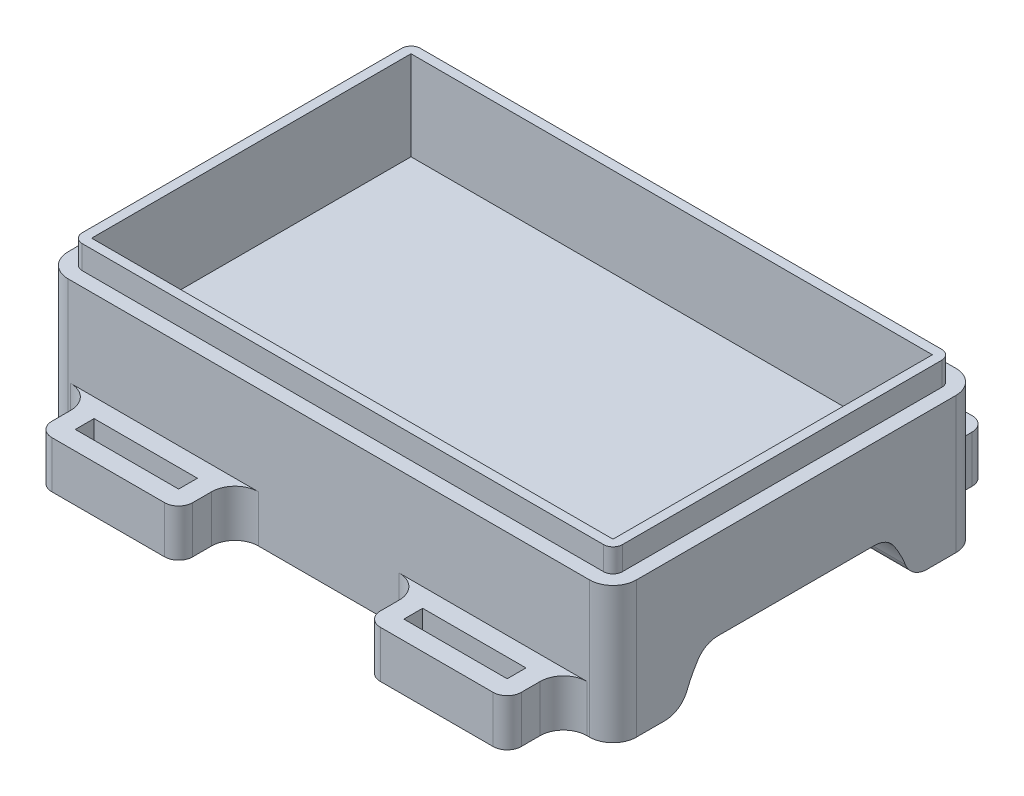
SolidWorks part; units mm, degrees
ref_plane "Alzado" through (0, 0, 0) normal (0, 0, 1) x (1, 0, 0)
ref_plane "Planta" through (0, 0, 0) normal (0, 1, 0) x (1, 0, 0)
ref_plane "Vista lateral" through (0, 0, 0) normal (1, 0, 0) x (0, 0, -1)
sketch "Croquis2" plane through (0, 0, 0) normal (0, 1, 0) x (1, 0, 0)
  line L1 (-55.5, 34) -> (55.5, 34)
  line L2 (-55.5, 34) -> (-55.5, -34)
  line L3 (-55.5, -34) -> (55.5, -34)
  line L4 (55.5, 34) -> (55.5, -34)
  line L12 (60.5, 39) -> (-60.5, 39)
  line L13 (-60.5, 39) -> (-60.5, -39)
  line L14 (-60.5, -39) -> (60.5, -39)
  line L15 (60.5, -39) -> (60.5, 39)
  point P4 (0, -34)
  point P6 (-55.5, 0)
  point P9 (0, -39)
  point P11 (-60.5, 0)
  point P13 (78.4837, 47.2518)
  dimension "D1" = 111
  dimension "D2" = 68
  dimension "D3" = 5
  dimension "D4" = 5
extrude "Saliente-Extruir2" add sketch "Croquis2" against normal blind 19
sketch "Croquis4" plane through (0, -19, 0) normal (0, -1, 0) x (1, 0, 0)
  line L4 (60.5, 39) -> (-60.5, 39)
  line L5 (-60.5, 39) -> (-60.5, -39)
  line L6 (-60.5, -39) -> (60.5, -39)
  line L7 (60.5, -39) -> (60.5, 39)
  line L8 (60.5, 39) -> (-60.5, 39)
  line L9 (-60.5, 39) -> (-60.5, -39)
  line L10 (-60.5, -39) -> (60.5, -39)
  line L11 (60.5, -39) -> (60.5, 39)
  dimension "D1" = 0
extrude "Saliente-Extruir3" add sketch "Croquis4" along normal blind 5
sketch "Croquis6" plane through (0, 0, 0) normal (1, 0, 0) x (0, 0, -1)
  line L0 (-19.2094, -24) -> (19.2094, -24) construction
  line L1 (-39, -24) -> (-19.2094, -24)
  line L2 (-39, -24) -> (-39, -34)
  line L3 (-39, -34) -> (-24.2693, -34)
  line L4 (39, -24) -> (39, -34)
  line L5 (19.2094, -24) -> (39, -24)
  line L6 (24.2693, -34) -> (39, -34)
  line L9 (39, -24) -> (-39, -24) construction
  circle A0 centre (0, -40) radius 25 construction
  arc A1 (-19.2094, -24) -> (-24.2693, -34) centre (0, -40) ccw
  arc A2 (19.2094, -24) -> (24.2693, -34) centre (0, -40) cw
  dimension "D2" = 50
  dimension "D1" = 40
  dimension "D3" = 10
extrude "Saliente-Extruir4" add sketch "Croquis6" along normal through all and the other way through all
fillet "Redondeo2" radius 5 4 edges at (0, -34, 24.2693) (0, -34, -24.2693) (0, -24, 19.2094) (0, -24, -19.2094)
sketch "Croquis7" plane through (0, -24, 0) normal (0, -1, 0) x (1, 0, 0)
  line L1 (-49.975, 39) -> (-19.975, 39)
  line L2 (-49.975, 39) -> (-49.975, 51)
  line L3 (-49.975, 51) -> (-19.975, 51)
  line L4 (-19.975, 39) -> (-19.975, 51)
  line L14 (0, 40) -> (0, -40) construction
  line L19 (-60.5, 0) -> (60.5, 0) construction
  line L20 (-60.5, 16.7033) -> (-60.5, -16.7033) construction
  line L21 (60.5, -16.7033) -> (60.5, 16.7033) construction
  line L22 (-49.975, -51) -> (-19.975, -51)
  line L23 (-19.975, -39) -> (-19.975, -51)
  line L24 (-49.975, -39) -> (-19.975, -39)
  line L25 (-49.975, -39) -> (-49.975, -51)
  line L26 (49.975, -39) -> (49.975, -51)
  line L27 (49.975, -39) -> (19.975, -39)
  line L28 (19.975, -39) -> (19.975, -51)
  line L29 (49.975, -51) -> (19.975, -51)
  line L30 (49.975, 51) -> (19.975, 51)
  line L31 (19.975, 39) -> (19.975, 51)
  line L32 (49.975, 39) -> (19.975, 39)
  line L33 (49.975, 39) -> (49.975, 51)
  line L34 (-45.975, -47) -> (-23.975, -47)
  line L35 (-23.975, -43) -> (-23.975, -47)
  line L36 (-45.975, -43) -> (-23.975, -43)
  line L37 (-45.975, -43) -> (-45.975, -47)
  line L38 (45.975, -43) -> (45.975, -47)
  line L39 (45.975, -47) -> (23.975, -47)
  line L40 (23.975, -43) -> (23.975, -47)
  line L41 (45.975, -43) -> (23.975, -43)
  line L42 (45.975, 47) -> (23.975, 47)
  line L43 (23.975, 43) -> (23.975, 47)
  line L44 (45.975, 43) -> (23.975, 43)
  line L45 (45.975, 43) -> (45.975, 47)
  line L46 (-45.975, 43) -> (-45.975, 47)
  line L47 (-45.975, 47) -> (-23.975, 47)
  line L48 (-23.975, 43) -> (-23.975, 47)
  line L49 (-45.975, 43) -> (-23.975, 43)
  line L51 (60.5, 39) -> (-60.5, 39) construction
  point P4 (0, 0)
  point P14 (0, 0)
  point P44 (0, 0)
  point P45 (0, 0)
  dimension "D1" = 30
  dimension "D2" = 12
  dimension "D3" = 20
  dimension "D5" = 80
  dimension "D4" = 4
extrude "Saliente-Extruir5" add sketch "Croquis7" along normal blind 10
fillet "Redondeo5" radius 3 8 edges at (49.975, -29, 51) (19.975, -29, 51) (-19.975, -29, 51) (-49.975, -29, 51) (-49.975, -29, -51) (19.975, -29, -51) (-19.975, -29, -51) (49.975, -29, -51)
fillet "Redondeo8" radius 5 4 edges at (-60.5, -17, -39) (-60.5, -17, 39) (60.5, -17, 39) (60.5, -17, -39)
fillet "Redondeo6" radius 5 8 edges at (-49.975, -29, -39) (19.975, -29, -39) (-19.975, -29, -39) (49.975, -29, -39) (49.975, -29, 39) (19.975, -29, 39) (-19.975, -29, 39) (-49.975, -29, 39)
sketch "Croquis8" plane through (0, 0, 0) normal (0, 1, 0) x (1, 0, 0)
  line L8 (55.5, 36) -> (-55.5, 36)
  line L9 (-57.5, 34) -> (-57.5, -34)
  line L10 (-55.5, -36) -> (55.5, -36)
  line L11 (57.5, -34) -> (57.5, 34)
  line L12 (55.5, 36) -> (-55.5, 36)
  line L13 (-57.5, 34) -> (-57.5, -34)
  line L14 (-55.5, -36) -> (55.5, -36)
  line L15 (57.5, -34) -> (57.5, 34)
  arc A8 (-55.5, 36) -> (-57.5, 34) centre (-55.5, 34) ccw
  arc A9 (-55.5, 36) -> (-57.5, 34) centre (-55.5, 34) ccw
  arc A10 (-57.5, -34) -> (-55.5, -36) centre (-55.5, -34) ccw
  arc A11 (-57.5, -34) -> (-55.5, -36) centre (-55.5, -34) ccw
  arc A12 (55.5, -36) -> (57.5, -34) centre (55.5, -34) ccw
  arc A13 (55.5, -36) -> (57.5, -34) centre (55.5, -34) ccw
  arc A14 (57.5, 34) -> (55.5, 36) centre (55.5, 34) ccw
  arc A15 (57.5, 34) -> (55.5, 36) centre (55.5, 34) ccw
  dimension "D1" = 3
extrude "Cortar-Extruir1" cut sketch "Croquis8" against normal blind 5 flip side to cut
